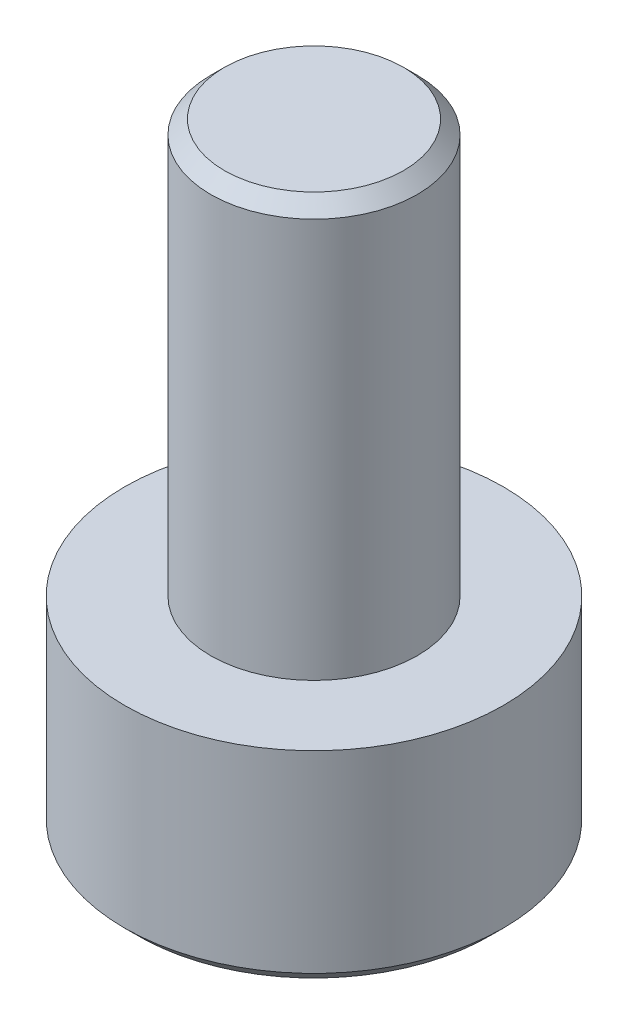
SolidWorks part; units mm, degrees
ref_plane "Front Plane" through (0, 0, 0) normal (0, 0, 1) x (1, 0, 0)
ref_plane "Top Plane" through (0, 0, 0) normal (0, 1, 0) x (1, 0, 0)
ref_plane "Right Plane" through (0, 0, 0) normal (1, 0, 0) x (0, 0, -1)
sketch "Reconstructed nominal axial profile" plane through (0, 0, 0) normal (0, 0, 1) x (1, 0, 0)
  line L0 (0, -500) -> (0, 50) construction
  line L1 (0, -3) -> (2.55, -3)
  line L2 (2.55, -3) -> (2.75, -2.8)
  line L3 (2.75, -2.8) -> (2.75, 0)
  line L4 (2.75, 0) -> (1.5, 0)
  line L5 (1.5, 0) -> (1.5, 5.8)
  line L6 (1.5, 5.8) -> (1.3, 6)
  line L7 (1.3, 6) -> (0, 6)
  line L8 (0, 6) -> (0, -3)
revolve "Native revolved geometry" add sketch "Reconstructed nominal axial profile" angle 360 about L0
sketch "Sketch2" plane through (0, 0, 0) normal (0, 1, 0) x (1, 0, 0)
  line L0 (1.4434, 0) -> (0.7217, -1.25)
  line L1 (0.7217, -1.25) -> (-0.7217, -1.25)
  line L2 (-0.7217, -1.25) -> (-1.4434, 0)
  line L3 (-1.4434, 0) -> (-0.7217, 1.25)
  line L4 (-0.7217, 1.25) -> (0.7217, 1.25)
  line L5 (0.7217, 1.25) -> (1.4434, 0)
extrude "Simplified nominal hex socket" cut sketch "Sketch2" along normal blind 1.5 from offset 3
